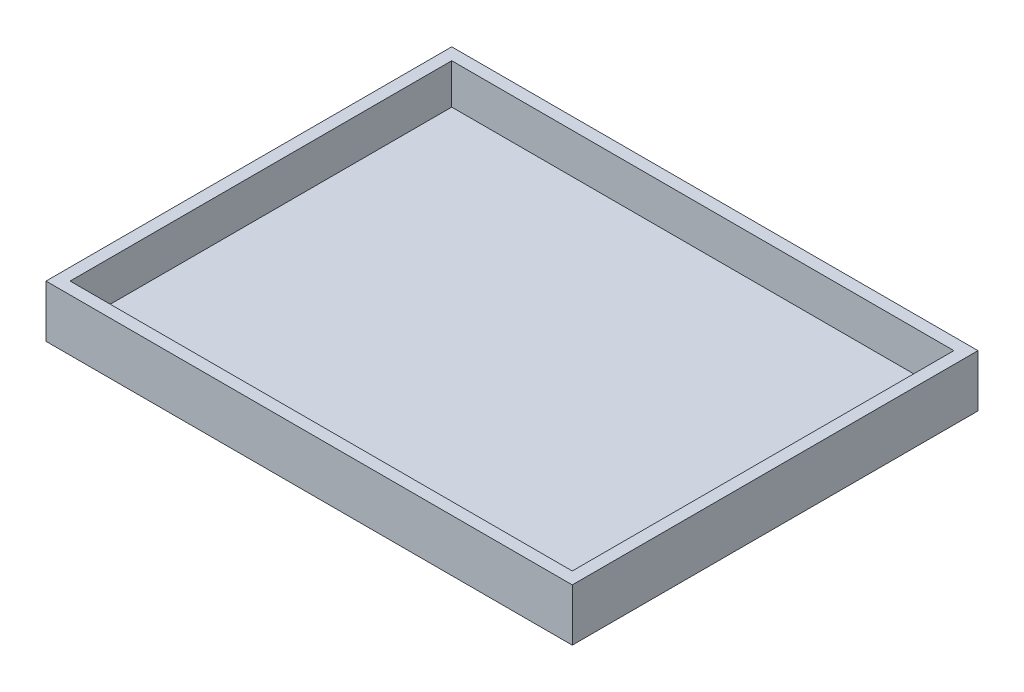
SolidWorks part; units mm, degrees
ref_plane "Front Plane" through (0, 0, 0) normal (0, 0, 1) x (1, 0, 0)
ref_plane "Top Plane" through (0, 0, 0) normal (0, 1, 0) x (1, 0, 0)
ref_plane "Right Plane" through (0, 0, 0) normal (1, 0, 0) x (0, 0, -1)
sketch "Sketch1" plane through (0, 0, 0) normal (0, 1, 0) x (1, 0, 0)
  line L1 (0, 0) -> (50, 0)
  line L2 (0, 0) -> (0, -38)
  line L3 (0, -38) -> (50, -38)
  line L4 (50, 0) -> (50, -38)
  dimension "D1" = 50
  dimension "D2" = 38
extrude "Boss-Extrude1" add sketch "Sketch1" along normal blind 4
shell "Shell1" thickness 1.2
